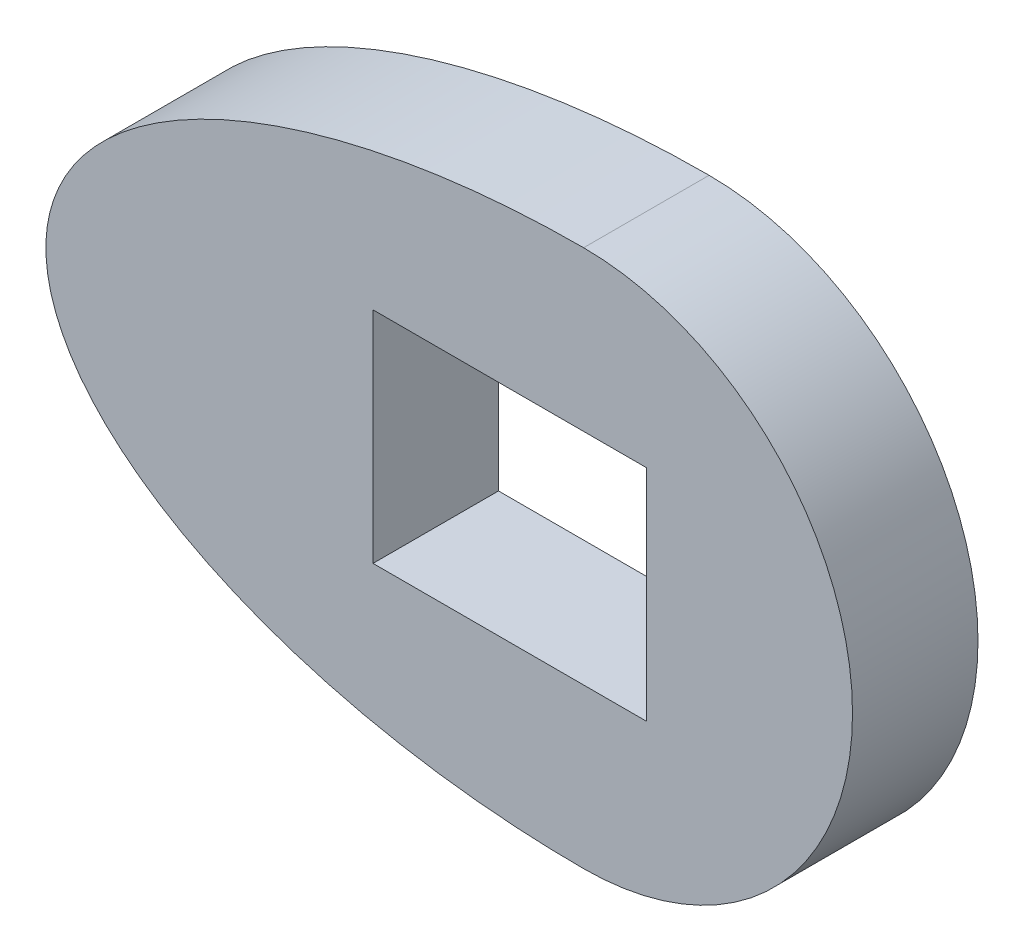
SolidWorks part; units mm, degrees
ref_plane "Front Plane" through (0, 0, 0) normal (0, 0, 1) x (1, 0, 0)
ref_plane "Top Plane" through (0, 0, 0) normal (0, 1, 0) x (1, 0, 0)
ref_plane "Right Plane" through (0, 0, 0) normal (1, 0, 0) x (0, 0, -1)
sketch "Sketch1" plane through (0, 0, 0) normal (0, 0, 1) x (1, 0, 0)
  arc A0 (0, -30) -> (0, 30) centre (0, 0) ccw
  ellipse E0 centre (0, 0) end of major axis (60, 0) minor radius 30 (0, 30) -> (0, -30) ccw
extrude "Boss-Extrude2" add sketch "Sketch1" along normal blind 14
sketch "Sketch2" plane through (0, 0, 0) normal (0, 0, -1) x (-1, 0, 0)
  line L1 (23.5, 12.25) -> (-7, 12.25)
  line L2 (23.5, 12.25) -> (23.5, -12.25)
  line L3 (23.5, -12.25) -> (-7, -12.25)
  line L4 (-7, 12.25) -> (-7, -12.25)
  line L5 (23.5, 12.25) -> (-7, -12.25) construction
  line L6 (23.5, -12.25) -> (-7, 12.25) construction
  point P0 (8.25, 0)
  dimension "D1" = 30.5
  dimension "D2" = 24.5
  dimension "D3" = 23.5
extrude "Cut-Extrude1" cut sketch "Sketch2" against normal up to surface (14 mm away) up to face at (-15, 0, 14)
